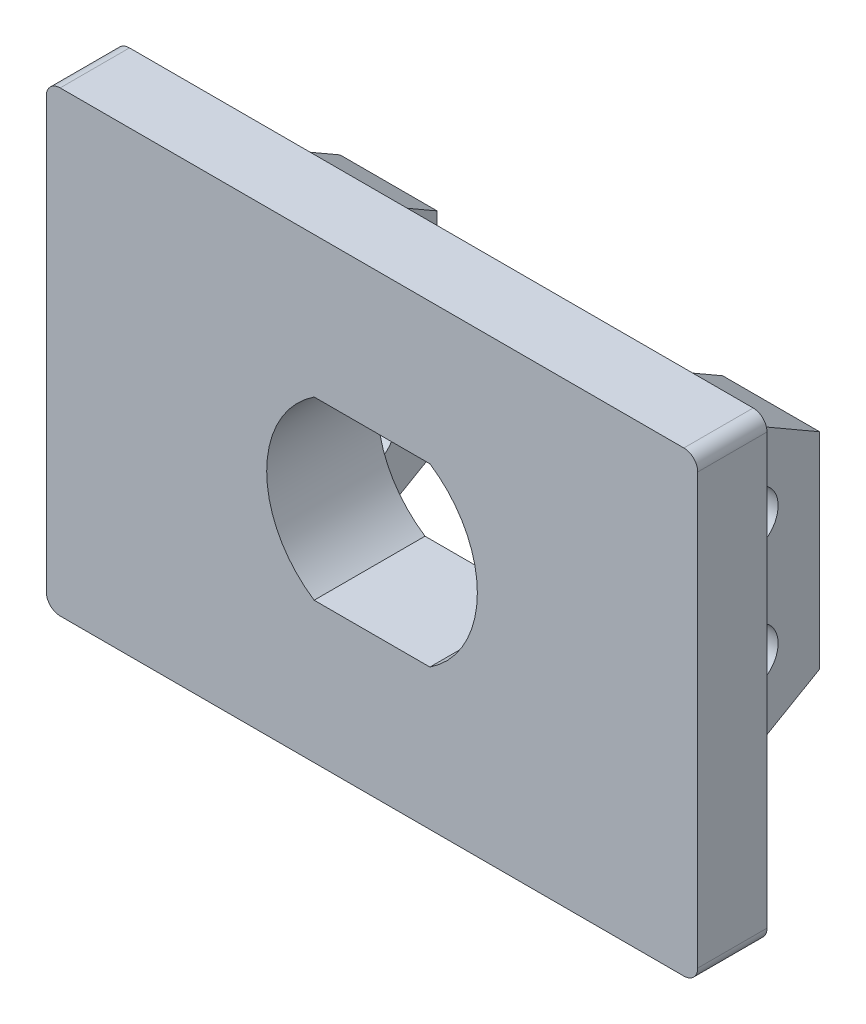
SolidWorks part; units mm, degrees
material "ABS"
ref_plane "Płaszczyzna przednia" through (0, 0, 0) normal (0, 0, 1) x (1, 0, 0)
ref_plane "Płaszczyzna górna" through (0, 0, 0) normal (0, 1, 0) x (1, 0, 0)
ref_plane "Płaszczyzna prawa" through (0, 0, 0) normal (1, 0, 0) x (0, 0, -1)
sketch "Szkic1" plane through (0, 0, 0) normal (0, 0, 1) x (1, 0, 0)
  line L0 (-4.1758, 6.35) -> (4.1758, 6.35)
  line L1 (-23.5, -16.5) -> (23.5, -16.5)
  line L2 (-23.5, -16.5) -> (-23.5, 16.5)
  line L3 (-23.5, 16.5) -> (23.5, 16.5)
  line L4 (23.5, -16.5) -> (23.5, 16.5)
  line L5 (-23.5, -16.5) -> (23.5, 16.5) construction
  line L6 (-23.5, 16.5) -> (23.5, -16.5) construction
  line L7 (-4.1758, -6.35) -> (4.1758, -6.35)
  circle A0 centre (0, 0) radius 7.6
  point P0 (0, 0)
  dimension "D3" = 15.2
  dimension "D1" = 33
  dimension "D2" = 47
  dimension "D4" = 12.7
extrude "Dodanie-wyciągnięcie1" add sketch "Szkic1" along normal blind 5 contours L0 A0 | L7 A0 | L1 L4 L3 L2 A0
sketch "Szkic2" plane through (0, 0, 0) normal (0, 0, -1) x (-1, 0, 0)
  line L1 (-17.3, -10.3) -> (-10.3, -10.3)
  line L2 (-17.3, -10.3) -> (-17.3, 10.3)
  line L3 (-17.3, 10.3) -> (-10.3, 10.3)
  line L4 (-10.3, -10.3) -> (-10.3, 10.3)
  line L5 (-17.3, -10.3) -> (-10.3, 10.3) construction
  line L6 (-17.3, 10.3) -> (-10.3, -10.3) construction
  line L7 (10.3, -10.3) -> (17.3, -10.3)
  line L8 (10.3, -10.3) -> (10.3, 10.3)
  line L9 (10.3, 10.3) -> (17.3, 10.3)
  line L10 (17.3, -10.3) -> (17.3, 10.3)
  line L11 (10.3, -10.3) -> (17.3, 10.3) construction
  line L12 (10.3, 10.3) -> (17.3, -10.3) construction
  line L13 (-23.5, -16.5) -> (-23.5, 16.5) construction
  line L17 (23.5, 16.5) -> (-23.5, 16.5) construction
  line L18 (23.5, -16.5) -> (-23.5, -16.5) construction
  line L19 (23.5, -16.5) -> (23.5, 16.5) construction
  point P0 (-13.8, 0)
  point P5 (13.8, 0)
  point P18 (-13.8, 0)
  dimension "D1" = 6.2
  dimension "D2" = 7
  dimension "D3" = 6.2
  dimension "D4" = 6.2
  dimension "D5" = 6.2
extrude "Dodanie-wyciągnięcie2" add sketch "Szkic2" along normal blind 10
chamfer "Sfazowanie1" distance 5 angle 30 4 edges at (13.8, 10.3, -10) (-13.8, 10.3, -10) (-13.8, -10.3, -10) (13.8, -10.3, -10)
sketch "Szkic3" plane through (17.3, 0, 0) normal (1, 0, 0) x (0, 0, -1)
  line L0 (0, -16.5) -> (0, 16.5) construction
  line L1 (5, -10.3) -> (0, -10.3) construction
  line L2 (5, 10.3) -> (0, 10.3) construction
  circle A0 centre (5, 4.3) radius 2
  circle A1 centre (5, -4.3) radius 2
  dimension "D1" = 4
  dimension "D2" = 5
  dimension "D3" = 6
  dimension "D4" = 6
extrude "Wytnij-wyciągnięcie1" cut sketch "Szkic3" against normal through all
fillet "Zaokrąglenie1" radius 1 4 edges at (-23.5, -16.5, 2.5) (23.5, -16.5, 2.5) (-23.5, 16.5, 2.5) (23.5, 16.5, 2.5)
sketch "Szkic5" plane through (0, 0, 0) normal (0, 0, -1) x (-1, 0, 0)
  line L0 (4.1758, -6.35) -> (-4.1758, -6.35) construction
  line L1 (4.1758, 6.35) -> (-4.1758, 6.35) construction
  line L2 (4.1758, -6.35) -> (-4.1758, -6.35)
  line L3 (4.1758, 6.35) -> (-4.1758, 6.35)
  line L4 (-10.3, 10.3) -> (-10.3, -10.3)
  line L5 (-10.3, -10.3) -> (10.3, -10.3)
  line L6 (10.3, -10.3) -> (10.3, 10.3)
  line L7 (10.3, 10.3) -> (-10.3, 10.3)
  arc A0 (4.1758, -6.35) -> (4.1758, 6.35) centre (0, 0) ccw construction
  arc A1 (-4.1758, 6.35) -> (-4.1758, -6.35) centre (0, 0) ccw construction
  arc A2 (4.1758, -6.35) -> (4.1758, 6.35) centre (0, 0) ccw
  arc A3 (-4.1758, 6.35) -> (-4.1758, -6.35) centre (0, 0) ccw
extrude "Dodanie-wyciągnięcie4" add sketch "Szkic5" along normal blind 3
